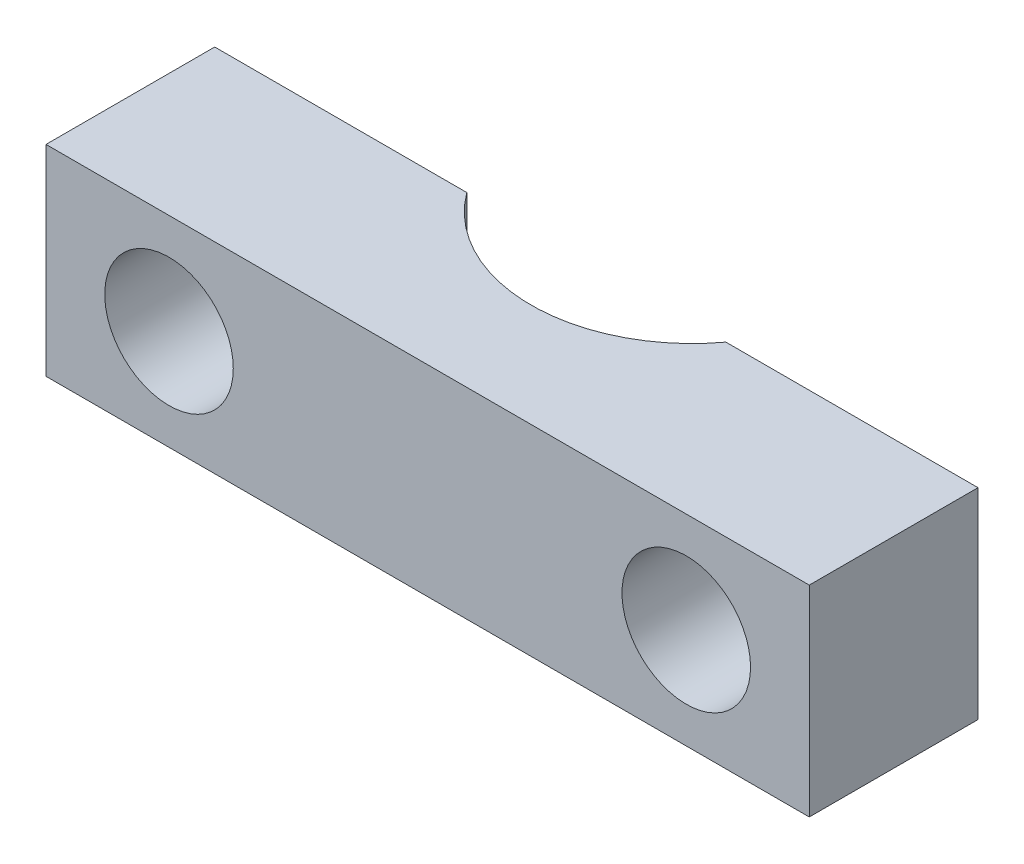
SolidWorks part; units mm, degrees
ref_plane "Alzado" through (0, 0, 0) normal (0, 0, 1) x (1, 0, 0)
ref_plane "Planta" through (0, 0, 0) normal (0, 1, 0) x (1, 0, 0)
ref_plane "Vista lateral" through (0, 0, 0) normal (1, 0, 0) x (0, 0, -1)
sketch "Croquis1" plane through (0, 0, 0) normal (0, 0, 1) x (1, 0, 0)
  line L1 (16.283, -33.1097) -> (35.283, -33.1097)
  line L2 (16.283, -33.1097) -> (16.283, -28.1097)
  line L3 (16.283, -28.1097) -> (35.283, -28.1097)
  line L4 (35.283, -33.1097) -> (35.283, -28.1097)
  circle A0 centre (19.3451, -30.6097) radius 1.6
  circle A1 centre (32.2209, -30.6097) radius 1.6
extrude "Saliente-Extruir1" add sketch "Croquis1" along normal blind 4.2
sketch "Croquis2" plane through (0, -33.1097, 0) normal (0, -1, 0) x (1, 0, 0)
  circle A0 centre (25.783, -2.3832) radius 4.0097
extrude "Cortar-Extruir1" cut sketch "Croquis2" against normal blind 7.2
